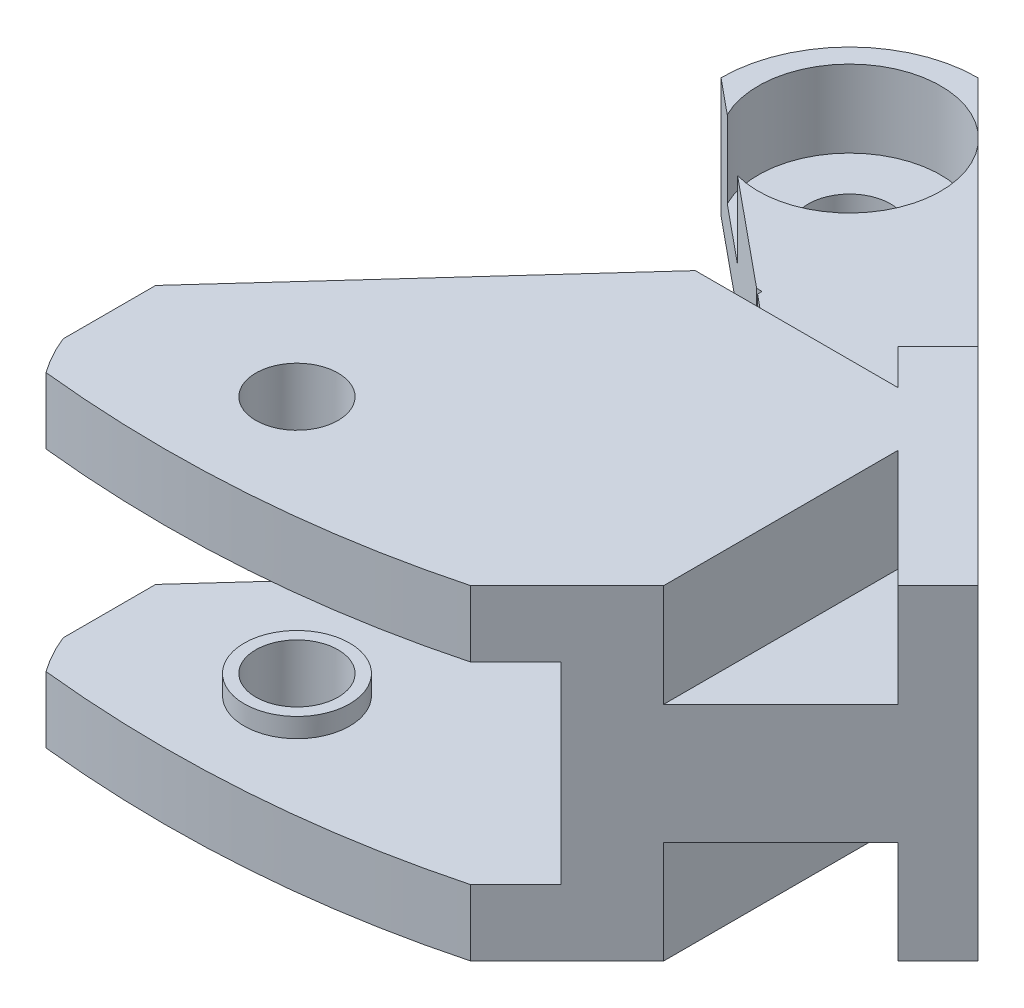
SolidWorks part; units mm, degrees
ref_plane "前视基准面" through (0, 0, 0) normal (0, 0, 1) x (1, 0, 0)
ref_plane "上视基准面" through (0, 0, 0) normal (0, 1, 0) x (1, 0, 0)
ref_plane "右视基准面" through (0, 0, 0) normal (1, 0, 0) x (0, 0, -1)
sketch "草图1" plane through (0, 0, 0) normal (0, 1, 0) x (1, 0, 0)
  line L0 (5, 0) -> (20, 0)
  line L1 (9, -16) -> (20, -16)
  line L3 (9, -16) -> (9, -35)
  line L4 (0, -35) -> (9, -35)
  line L5 (0, -27) -> (0, -5)
  line L6 (0, -27) -> (0, -35)
  line L7 (20, -16) -> (20, 0)
  circle A0 centre (4.55, -4.55) radius 1.6
  arc A1 (5, 0) -> (0, -5) centre (5, -5) ccw
  point P11 (0, 0)
extrude "凸台-拉伸1" add sketch "草图1" along normal blind 4.65
sketch "草图7" plane through (0, 4.65, 0) normal (0, 1, 0) x (1, 0, 0)
  line L0 (9, -35) -> (9, -16) construction
  line L1 (0, -35) -> (9, -35)
  line L2 (0, -35) -> (0, -16)
  line L3 (0, -16) -> (9, -16)
  line L4 (9, -35) -> (9, -16)
extrude "凸台-拉伸4" add sketch "草图7" along normal blind 4
sketch "草图8" plane through (0, 0, 0) normal (0, -1, 0) x (1, 0, 0)
  line L0 (0, 5) -> (0, 35) construction
  line L1 (0, 35) -> (9, 35)
  line L2 (0, 35) -> (0, 16)
  line L3 (0, 16) -> (9, 16)
  line L4 (9, 35) -> (9, 16)
  line L5 (9, 35) -> (9, 16) construction
extrude "凸台-拉伸5" add sketch "草图8" along normal blind 4
sketch "草图9" plane through (0, 0, 0) normal (-1, 0, 0) x (0, 0, 1)
  line L0 (35, 8.65) -> (35, -4) construction
  line L1 (35, 6.075) -> (19, 6.075)
  line L2 (35, 6.075) -> (35, -1.425)
  line L3 (35, -1.425) -> (19, -1.425)
  line L4 (19, 6.075) -> (19, -1.425)
extrude "切除-拉伸3" cut sketch "草图9" against normal blind 9
sketch "草图11" plane through (0, 8.65, 0) normal (0, 1, 0) x (1, 0, 0)
  circle A1 centre (6.5, -28) radius 1.6
  dimension "D1" = 3.2
extrude "切除-拉伸5" cut sketch "草图11" against normal blind 26.4
sketch "草图12" plane through (9, 0, 0) normal (1, 0, 0) x (0, 0, -1)
  line L0 (-35, 8.65) -> (-35, 6.075)
  line L1 (-35, 6.075) -> (-19, 6.075)
  line L2 (-19, 6.075) -> (-19, -1.425)
  line L3 (-19, -1.425) -> (-35, -1.425)
  line L4 (-35, -1.425) -> (-35, -4)
  line L5 (-35, -4) -> (-16, -4)
  line L6 (-16, -4) -> (-16, 8.65)
  line L7 (-16, 8.65) -> (-35, 8.65)
extrude "凸台-拉伸6" add sketch "草图12" along normal blind 9
sketch "草图13" plane through (18, 0, 0) normal (1, 0, 0) x (0, 0, -1)
  line L0 (-35, 8.65) -> (-35, -4)
  line L1 (-35, -4) -> (-16, -4)
  line L2 (-16, -4) -> (-16, 8.65)
  line L3 (-16, 8.65) -> (-35, 8.65)
extrude "凸台-拉伸7" add sketch "草图13" along normal blind 2
sketch "草图15" plane through (0, 0, 0) normal (-1, 0, 0) x (0, 0, 1)
  line L2 (19, -1.425) -> (11.4034, -1.425)
  line L3 (19, -1.425) -> (19, 6.075)
  line L4 (19, 6.075) -> (11.4034, 6.075)
  line L7 (11.4034, -1.425) -> (11.4034, 6.075)
extrude "切除-拉伸6" cut sketch "草图15" against normal blind 8
sketch "草图16" plane through (0, 4.65, 0) normal (0, 1, 0) x (1, 0, 0)
  line L0 (0, -5) -> (5.8909, -11.4034)
  line L1 (8, -11.4034) -> (0, -11.4034) construction
  line L2 (5.8909, -11.4034) -> (0, -11.4034)
  line L3 (0, -11.4034) -> (0, -5)
extrude "切除-拉伸7" cut sketch "草图16" against normal blind 8
sketch "草图17" plane through (0, 0, 0) normal (0, -1, 0) x (1, 0, 0)
  line L1 (20, 35) -> (20, 15)
  line L3 (31.0646, 26.0646) -> (20, 15)
  arc A0 (20, 35) -> (31.0646, 26.0646) centre (4.55, 4.55) cw
extrude "凸台-拉伸8" add sketch "草图17" against normal blind 4.65
sketch "草图19" plane through (0, 4.65, 0) normal (0, 1, 0) x (1, 0, 0)
  line L0 (20, -15) -> (5, 0)
  line L1 (5, 0) -> (20, 0)
  line L2 (20, 0) -> (20, -15)
extrude "切除-拉伸9" cut sketch "草图19" against normal blind 4.65
sketch "草图20" plane through (0, -1.425, 0) normal (0, 1, 0) x (1, 0, 0)
  line L0 (8, -19) -> (8, -16)
  line L1 (8, -16) -> (13.3802, -16)
  line L2 (13.3802, -16) -> (13.3802, -19)
  line L3 (18, -19) -> (8, -19) construction
  line L4 (13.3802, -19) -> (8, -19)
extrude "切除-拉伸10" cut sketch "草图20" along normal blind 7.5
sketch "草图21" plane through (0, 0, 0) normal (0, -1, 0) x (1, 0, 0)
  line L0 (13.3802, 16) -> (0, 5)
  line L1 (0, 5) -> (8, 16)
  line L2 (8, 11.4034) -> (8, 16) construction
  line L3 (8, 16) -> (13.3802, 16) construction
  line L4 (8, 16) -> (13.3802, 16)
  arc A0 (0, 5) -> (5, 0) centre (5, 5) ccw construction
extrude "切除-拉伸11" cut sketch "草图21" against normal blind 4.65
sketch "草图22" plane through (0, 8.65, 0) normal (0, 1, 0) x (1, 0, 0)
  line L0 (0, -16) -> (10, -16)
  line L1 (20, -16) -> (0, -16) construction
  line L2 (10, -16) -> (0, -27)
  line L3 (0, -16) -> (0, -35) construction
  line L4 (0, -27) -> (0, -16)
extrude "切除-拉伸13" cut sketch "草图22" against normal blind 13
sketch "草图23" plane through (0, 8.65, 0) normal (0, 1, 0) x (1, 0, 0)
  line L0 (6.5, -35) -> (0, -35)
  line L1 (0, -35) -> (0, -30.5981)
  line L2 (0, -27) -> (0, -35) construction
  arc A0 (0, -30.5981) -> (6.5, -35) centre (6.5, -28) ccw
extrude "切除-拉伸15" cut sketch "草图23" against normal blind 13
sketch "草图26" plane through (2.5, 0, -2.5) normal (0.7071, 0, -0.7071) x (-0.7071, 0, -0.7071)
  line L1 (-40.3965, 8.65) -> (-22, 8.65)
  line L2 (-40.3965, 8.65) -> (-40.3965, -4)
  line L3 (-40.3965, -4) -> (-22, -4)
  line L4 (-22, 8.65) -> (-22, -4)
extrude "凸台-拉伸9" add sketch "草图26" against normal blind 2.2
sketch "草图28" plane through (2.5, 0, -2.5) normal (0.7071, 0, -0.7071) x (-0.7071, 0, -0.7071)
  line L0 (-22, 8.65) -> (-40.3965, 8.65) construction
  line L1 (-40.8965, -4) -> (-38.3965, -4)
  line L2 (-40.8965, -4) -> (-40.8965, 8.65)
  line L3 (-40.8965, 8.65) -> (-38.3965, 8.65)
  line L4 (-38.3965, -4) -> (-38.3965, 8.65)
extrude "切除-拉伸17" cut sketch "草图28" against normal blind 18
sketch "草图29" plane through (0, -4, 0) normal (0, -1, 0) x (1, 0, 0)
  line L0 (29.6504, 24.6504) -> (19.3008, 35)
  line L1 (19.3008, 35) -> (1.7736, 35)
  line L2 (1.7736, 35) -> (0.8039, 32.0688)
  arc A1 (6.5, 35) -> (0, 30.5981) centre (6.5, 28) ccw construction
  spline S0 degree 2 poles (29.6504, 24.6504) (16.7115, 33.7569) (0.8039, 32.0688) knots 0 0 0 1 1 1
extrude "切除-拉伸18" cut sketch "草图29" against normal blind 14
sketch "草图31" plane through (2.5, 0, -2.5) normal (0.7071, 0, -0.7071) x (-0.7071, 0, -0.7071)
  line L0 (-38.3965, -4) -> (-22, -4) construction
  line L1 (-38.3965, 8.65) -> (-33.3965, 8.65)
  line L2 (-38.3965, 8.65) -> (-38.3965, -4)
  line L3 (-38.3965, -4) -> (-33.3965, -4)
  line L4 (-33.3965, 8.65) -> (-33.3965, -4)
extrude "切除-拉伸19" cut sketch "草图31" against normal blind 20
sketch "草图32" plane through (0, 4.65, 0) normal (0, 1, 0) x (1, 0, 0)
  circle A0 centre (4.55, -4.55) radius 3.55
  dimension "D1" = 7.1
extrude "切除-拉伸20" cut sketch "草图32" against normal blind 3 contours A0
sketch "草图33" plane through (0, -1.425, 0) normal (0, 1, 0) x (1, 0, 0)
  circle A0 centre (6.5, -28) radius 2.05
  circle A1 centre (6.5, -28) radius 1.6
  dimension "D1" = 4.1
extrude "凸台-拉伸10" add sketch "草图33" along normal blind 0.75
sketch "草图34" plane through (0, 6.075, 0) normal (0, -1, 0) x (1, 0, 0)
  circle A0 centre (6.5, 28) radius 1.6
  circle A1 centre (6.5, 28) radius 2.05
  dimension "D1" = 4.1
extrude "凸台-拉伸11" add sketch "草图34" along normal blind 0.75
